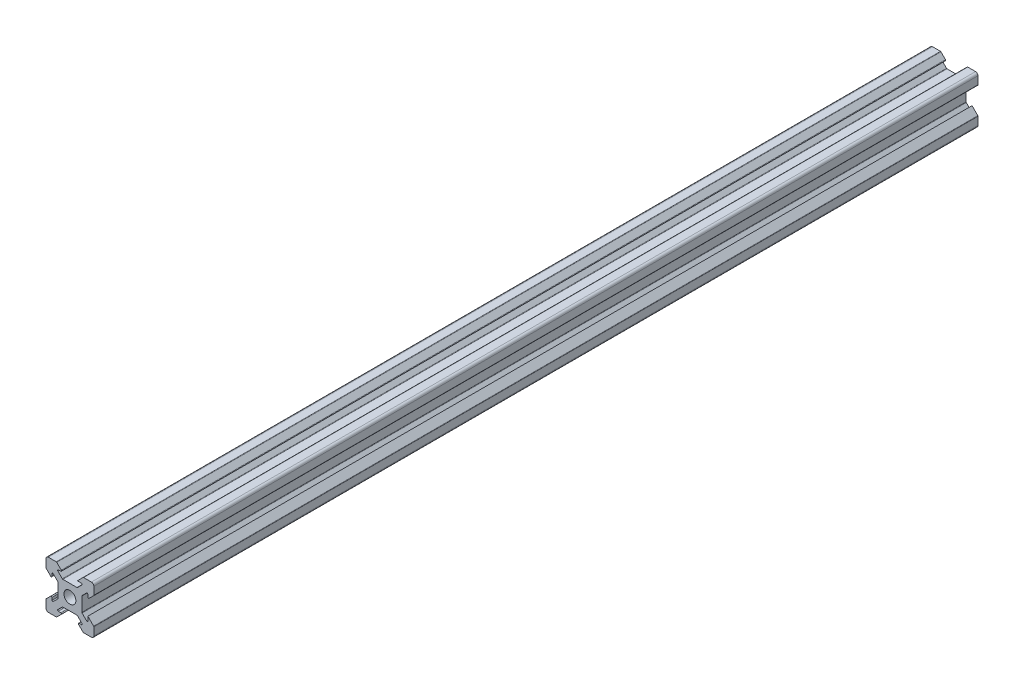
SolidWorks part; units mm, degrees
ref_plane "Alzado" through (0, 0, 0) normal (0, 0, 1) x (1, 0, 0)
ref_plane "Planta" through (0, 0, 0) normal (0, 1, 0) x (1, 0, 0)
ref_plane "Vista lateral" through (0, 0, 0) normal (1, 0, 0) x (0, 0, -1)
sketch "Croquis1" plane through (0, 0, 0) normal (0, 1, 0) x (1, 0, 0)
  line L0 (0, 185) -> (0, -185)
  dimension "D1" = 370
other "Miembro estructural1"
ref_plane "Plano1" through (0, 0, -185) normal (0, 0, 1) x (1, 0, 0)
sketch "Croquis11" plane through (0, 0, -185) normal (0, 0, 1) x (1, 0, 0)
  line L0 (0, 10) -> (0, -10) construction
  line L1 (-9, -10) -> (-5.714, -10)
  line L2 (-10, -9) -> (-10, -5.714)
  line L3 (-9, 10) -> (-5.714, 10)
  line L4 (10, -9) -> (10, -5.714)
  line L5 (-10, -10) -> (10, 10) construction
  line L6 (-10, 10) -> (10, -10) construction
  line L7 (-10, 0) -> (10, 0) construction
  line L8 (-5.5019, 9.9121) -> (-3.6121, 8.0224)
  line L9 (-3.8243, 7.5103) -> (-4.8471, 7.5103)
  line L10 (-5.0593, 6.9981) -> (-3.1695, 5.1084)
  line L11 (-2.9574, 5.0205) -> (2.9574, 5.0205)
  line L12 (3.1, 7.5103) -> (4.8471, 7.5103)
  line L13 (5.0593, 6.9981) -> (3.1695, 5.1084)
  line L14 (5.5019, 9.9121) -> (3.1, 7.5103)
  line L15 (5.714, 10) -> (9, 10)
  line L16 (9.9121, 5.5019) -> (8.0224, 3.6121)
  line L17 (7.5103, 3.8243) -> (7.5103, 4.8471)
  line L18 (6.9981, 5.0593) -> (5.1084, 3.1695)
  line L19 (5.0205, 2.9574) -> (5.0205, -2.9574)
  line L20 (6.9981, -5.0593) -> (5.1084, -3.1695)
  line L21 (7.5103, -3.1) -> (7.5103, -4.8471)
  line L22 (9.9121, -5.5019) -> (7.5103, -3.1)
  line L23 (5.5019, -9.9121) -> (3.6121, -8.0224)
  line L24 (3.8243, -7.5103) -> (4.8471, -7.5103)
  line L25 (5.0593, -6.9981) -> (3.1695, -5.1084)
  line L26 (2.9574, -5.0205) -> (-2.9574, -5.0205)
  line L27 (-5.0593, -6.9981) -> (-3.1695, -5.1084)
  line L28 (-3.8243, -7.5103) -> (-4.8471, -7.5103)
  line L29 (-5.5019, -9.9121) -> (-3.6121, -8.0224)
  line L30 (-9.9121, -5.5019) -> (-8.0224, -3.6121)
  line L31 (-7.5103, -3.8243) -> (-7.5103, -4.8471)
  line L32 (-6.9981, -5.0593) -> (-5.1084, -3.1695)
  line L33 (-5.0205, -2.9574) -> (-5.0205, 2.9574)
  line L34 (-6.9981, 5.0593) -> (-5.1084, 3.1695)
  line L35 (-7.5103, 3.8243) -> (-7.5103, 4.8471)
  line L36 (-9.9121, 5.5019) -> (-8.0224, 3.6121)
  line L37 (-10, 5.714) -> (-10, 9)
  line L38 (10, 5.714) -> (10, 9)
  line L39 (5.714, -10) -> (9, -10)
  circle A0 centre (0, 0) radius 2.5
  arc A1 (5.5019, 9.9121) -> (5.714, 10) centre (5.714, 9.7) cw
  arc A2 (9.9121, 5.5019) -> (10, 5.714) centre (9.7, 5.714) ccw
  arc A3 (9.9121, -5.5019) -> (10, -5.714) centre (9.7, -5.714) cw
  arc A4 (5.5019, -9.9121) -> (5.714, -10) centre (5.714, -9.7) ccw
  arc A5 (-5.5019, -9.9121) -> (-5.714, -10) centre (-5.714, -9.7) cw
  arc A6 (-9.9121, -5.5019) -> (-10, -5.714) centre (-9.7, -5.714) ccw
  arc A7 (-5.5019, 9.9121) -> (-5.714, 10) centre (-5.714, 9.7) ccw
  arc A8 (-3.6121, 8.0224) -> (-3.8243, 7.5103) centre (-3.8243, 7.8103) cw
  arc A9 (-4.8471, 7.5103) -> (-5.0593, 6.9981) centre (-4.8471, 7.2103) ccw
  arc A10 (-3.1695, 5.1084) -> (-2.9574, 5.0205) centre (-2.9574, 5.3205) ccw
  arc A11 (3.1695, 5.1084) -> (2.9574, 5.0205) centre (2.9574, 5.3205) cw
  arc A12 (4.8471, 7.5103) -> (5.0593, 6.9981) centre (4.8471, 7.2103) cw
  arc A13 (8.0224, 3.6121) -> (7.5103, 3.8243) centre (7.8103, 3.8243) cw
  arc A14 (7.5103, 4.8471) -> (6.9981, 5.0593) centre (7.2103, 4.8471) ccw
  arc A15 (5.1084, 3.1695) -> (5.0205, 2.9574) centre (5.3205, 2.9574) ccw
  arc A16 (5.0205, -2.9574) -> (5.1084, -3.1695) centre (5.3205, -2.9574) ccw
  arc A17 (6.9981, -5.0593) -> (7.5103, -4.8471) centre (7.2103, -4.8471) ccw
  arc A18 (3.6121, -8.0224) -> (3.8243, -7.5103) centre (3.8243, -7.8103) cw
  arc A19 (4.8471, -7.5103) -> (5.0593, -6.9981) centre (4.8471, -7.2103) ccw
  arc A20 (3.1695, -5.1084) -> (2.9574, -5.0205) centre (2.9574, -5.3205) ccw
  arc A21 (-3.8243, -7.5103) -> (-3.6121, -8.0224) centre (-3.8243, -7.8103) cw
  arc A22 (-2.9574, -5.0205) -> (-3.1695, -5.1084) centre (-2.9574, -5.3205) ccw
  arc A23 (-5.0593, -6.9981) -> (-4.8471, -7.5103) centre (-4.8471, -7.2103) ccw
  arc A24 (-8.0224, -3.6121) -> (-7.5103, -3.8243) centre (-7.8103, -3.8243) cw
  arc A25 (-7.5103, -4.8471) -> (-6.9981, -5.0593) centre (-7.2103, -4.8471) ccw
  arc A26 (-5.1084, -3.1695) -> (-5.0205, -2.9574) centre (-5.3205, -2.9574) ccw
  arc A27 (-5.0205, 2.9574) -> (-5.1084, 3.1695) centre (-5.3205, 2.9574) ccw
  arc A28 (-6.9981, 5.0593) -> (-7.5103, 4.8471) centre (-7.2103, 4.8471) ccw
  arc A29 (-7.5103, 3.8243) -> (-8.0224, 3.6121) centre (-7.8103, 3.8243) cw
  arc A30 (-9.9121, 5.5019) -> (-10, 5.714) centre (-9.7, 5.714) cw
  arc A31 (-9, -10) -> (-10, -9) centre (-9, -9) cw
  arc A32 (9, -10) -> (10, -9) centre (9, -9) ccw
  arc A33 (9, 10) -> (10, 9) centre (9, 9) cw
  arc A34 (-10, 9) -> (-9, 10) centre (-9, 9) cw
  point P0 (0, 0)
  point P18 (0, 5.0205)
  point P23 (5.5897, 10)
  point P48 (0, 0)
  point P61 (-5.5897, 10)
  point P64 (-3.1, 7.5103)
  point P67 (-5.5714, 7.5103)
  point P70 (-3.0817, 5.0205)
  point P73 (3.0817, 5.0205)
  point P76 (5.5714, 7.5103)
  point P125 (0, 0)
  dimension "D3" = 5
  dimension "D7" = 0.3
  dimension "D8" = 1
  dimension "D1" = 20
  dimension "D2" = 20
  dimension "D4" = 3.1
  dimension "D5" = 45
  dimension "D6" = 4
